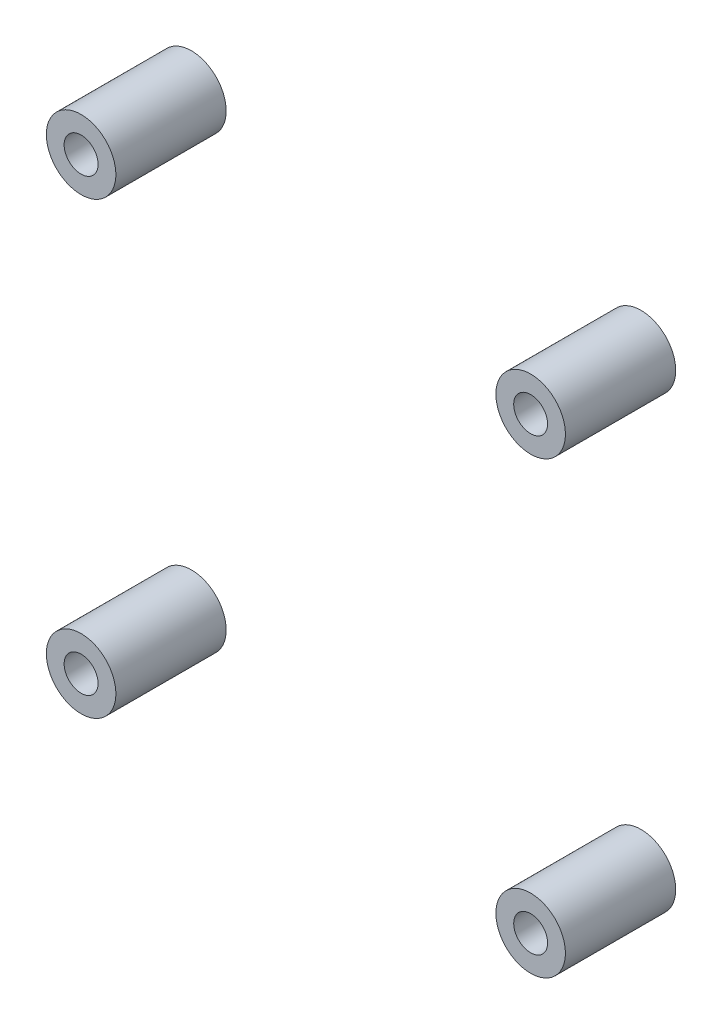
SolidWorks part; units mm, degrees
material "黄铜"
ref_plane "前视基准面" through (0, 0, 0) normal (0, 0, 1) x (1, 0, 0)
ref_plane "上视基准面" through (0, 0, 0) normal (0, 1, 0) x (1, 0, 0)
ref_plane "右视基准面" through (0, 0, 0) normal (1, 0, 0) x (0, 0, -1)
sketch "草图1" plane through (0, 0, 0) normal (0, 0, 1) x (1, 0, 0)
  circle A0 centre (-40.9973, 14.7867) radius 1.2295
  circle A1 centre (-40.9973, 14.7867) radius 2.52
  circle A2 centre (-8.3997, 14.7867) radius 1.2295
  circle A3 centre (-8.3997, 14.7867) radius 2.52
  circle A4 centre (-8.3997, -17.811) radius 1.2295
  circle A5 centre (-8.3997, -17.811) radius 2.52
  circle A6 centre (-40.9973, -17.811) radius 1.2295
  circle A7 centre (-40.9973, -17.811) radius 2.52
  point P17 (-24.6985, -1.5122)
  dimension "D1" = 4
extrude "凸台-拉伸1" add sketch "草图1" against normal blind 8 from surface at -32.8004
